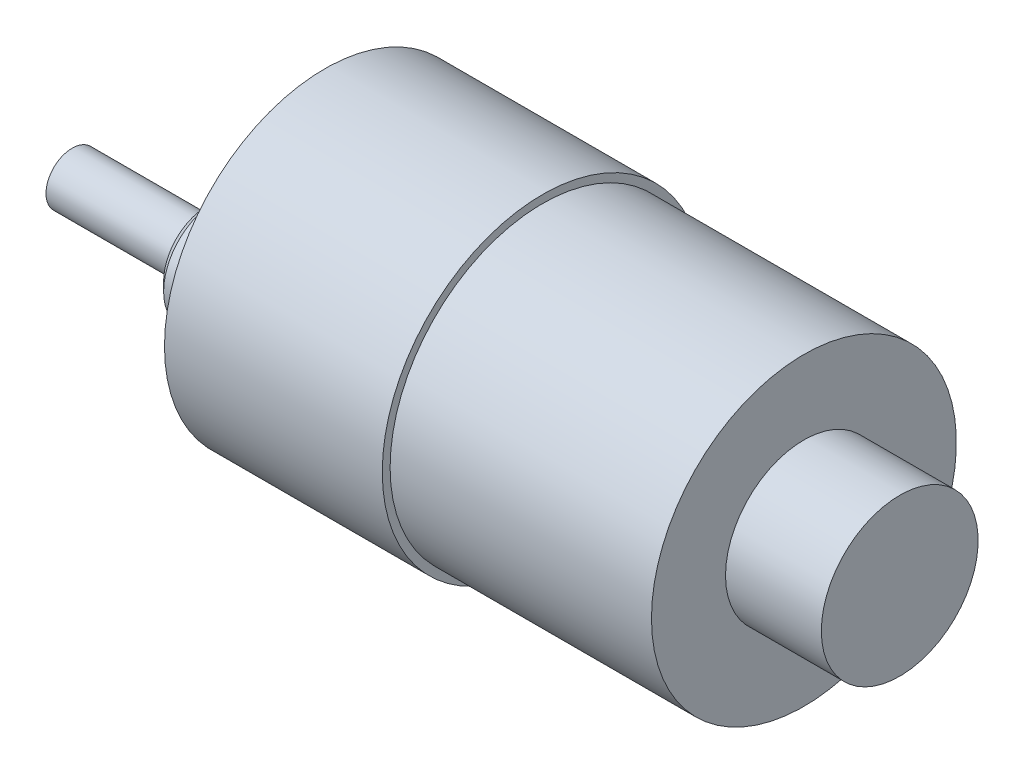
SolidWorks part; units mm, degrees
ref_plane "Plan de face" through (0, 0, 0) normal (0, 0, 1) x (1, 0, 0)
ref_plane "Plan de dessus" through (0, 0, 0) normal (0, 1, 0) x (1, 0, 0)
ref_plane "Plan de droite" through (0, 0, 0) normal (1, 0, 0) x (0, 0, -1)
sketch "Esquisse1" plane through (0, 0, 0) normal (0, 0, 1) x (1, 0, 0)
  line L0 (12.5, 0) -> (1014.7804, 0) construction
  line L1 (0, 6) -> (0, 0)
  line L2 (0, 0) -> (12.5, 0)
  line L4 (25, 18.4) -> (0, 18.4)
  line L6 (12.5, 0) -> (0, 18.4) construction
  line L7 (25, 18.4) -> (12.5, 0) construction
  line L9 (55, 0) -> (55, 17.5)
  line L10 (55, 17.5) -> (25, 17.5)
  line L11 (12.5, 0) -> (55, 0)
  line L12 (40, 0) -> (25, 17.5) construction
  line L13 (55, 17.5) -> (40, 0) construction
  line L17 (25, 17.5) -> (25, 18.4)
  line L23 (0, 6) -> (0, 18.4)
  point P1 (12.5, 0)
  point P9 (40, 0)
  dimension "D1" = 17.5
  dimension "D2" = 30
  dimension "D3" = 18.4
  dimension "D4" = 25
revolve "Révolution10" add sketch "Esquisse1" angle 360 about L0
ref_plane "Plan1" through (0, 0, 7) normal (0, 0, 1) x (1, 0, 0)
sketch "Esquisse3" plane through (0, 0, 7) normal (0, 0, 1) x (1, 0, 0)
  line L0 (0, 0) -> (38.5247, 0) construction
  line L2 (0, 0) -> (-6.5, 0)
  line L3 (0, 0) -> (0, 6)
  line L4 (0, 6) -> (-6.5, 6)
  line L5 (-6.5, 0) -> (-6.5, 6)
  line L6 (-6.5, 0) -> (-22, 0)
  line L7 (-6.5, 0) -> (-6.5, 3)
  line L8 (-6.5, 3) -> (-22, 3)
  line L9 (-22, 0) -> (-22, 3)
  dimension "D1" = 6.5
  dimension "D2" = 6
  dimension "D3" = 15.5
  dimension "D4" = 3
revolve "Révolution12" add sketch "Esquisse3" angle 360 about L0
chamfer "Chanfrein1" distance 1 angle 45 1 edges at (-6.5, 0, 13)
sketch "Esquisse4" plane through (-22, 0, 0) normal (-1, 0, 0) x (0, 0, 1)
  line L0 (5.2, -2.4) -> (8.8, -2.4)
  circle A1 centre (7, 0) radius 3
  circle A2 centre (7, 0) radius 3
  dimension "D2" = 2.4
  dimension "D1" = 0
extrude "Enlèv. mat.-Extru.1" cut sketch "Esquisse4" against normal blind 12 and the other way through all flip side to cut contours L0
hole_wizard "Trou pour taraudage pour trou taraudé M3x0.51" positions "Esquisse8" profile "Esquisse7" hole size "M3x0.5" standard "Ansi Metric"
sketch "Esquisse8" plane through (0, 0, 0) normal (-1, 0, 0) x (0, 0, 1)
  line L1 (-13.4234, -7.75) -> (0, -15.5)
  line L2 (0, -15.5) -> (13.4234, -7.75)
  line L3 (13.4234, -7.75) -> (13.4234, 7.75)
  line L4 (13.4234, 7.75) -> (0, 15.5)
  line L5 (0, 15.5) -> (-13.4234, 7.75)
  line L6 (-13.4234, 7.75) -> (-13.4234, -7.75)
  line L7 (0, 0) -> (0, 20.0536) construction
  circle A0 centre (0, 0) radius 13.4234 construction
  point P0 (0, 15.5)
  point P5 (-13.4234, -7.75)
  point P6 (0, -15.5)
  point P7 (13.4234, -7.75)
  point P8 (13.4234, 7.75)
  point P10 (-13.4234, 7.75)
  dimension "D1" = 31
sketch "Esquisse7" plane through (0, 15.5, 0) normal (0, 1, 0) x (0, 0, 1)
  line L0 (0, 0) -> (0, 15.7511)
  line L1 (0, 15.7511) -> (1.25, 15)
  line L2 (1.25, 15) -> (1.25, 0)
  line L5 (1.25, 0) -> (0, 0)
  line L10 (0, 15.7511) -> (-1.25, 15) construction
  line L11 (0, -6.35) -> (0, 107.95) construction
  dimension "Diamètre du perçage" = 2.5
  dimension "Profondeur du perçage" = 15
  dimension "Angle de pointe" = 118
sketch "Esquisse9" plane through (0, 0, 0) normal (0, 0, 1) x (1, 0, 0)
  line L0 (0, 0) -> (72.6266, 0) construction
  line L1 (55, -17.5) -> (55, 17.5) construction
  line L2 (55, 0) -> (66, 0)
  line L3 (55, 0) -> (55, 9)
  line L4 (55, 9) -> (66, 9)
  line L5 (66, 0) -> (66, 9)
  dimension "D1" = 9
  dimension "D2" = 11
revolve "Révolution13" add sketch "Esquisse9" angle 360 about L0
